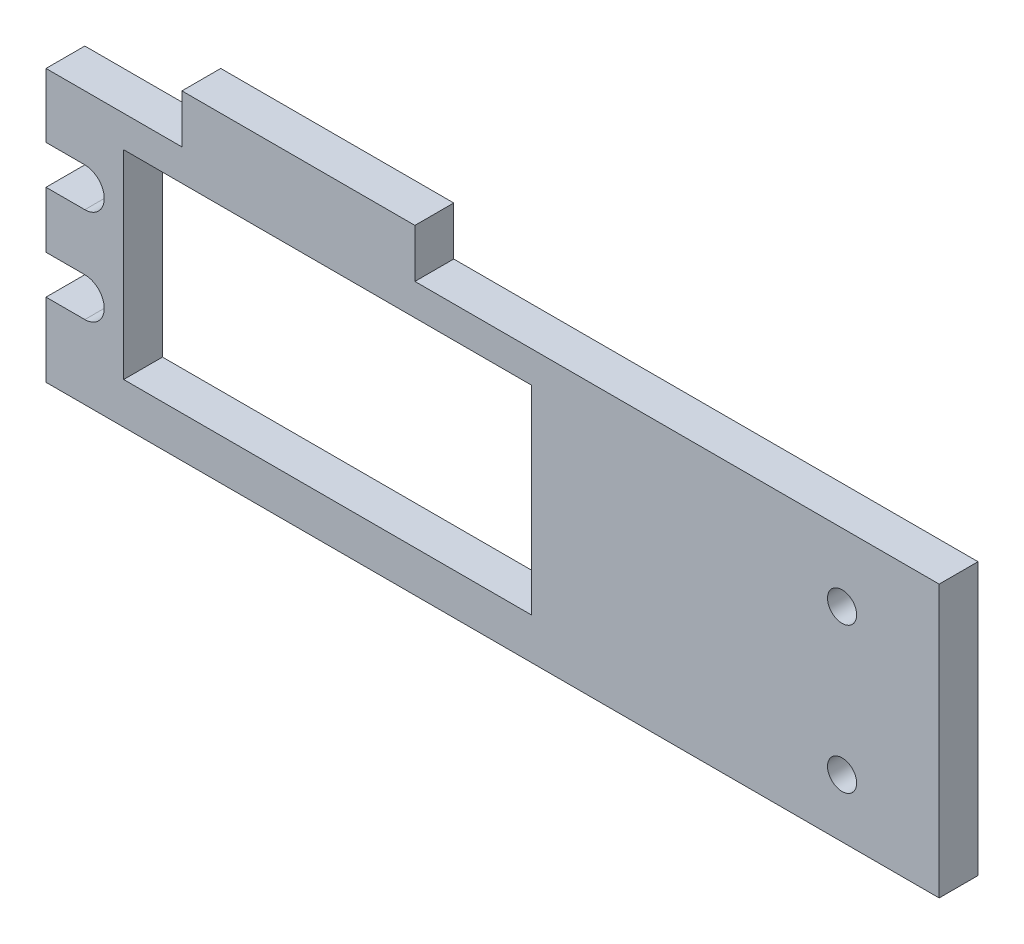
SolidWorks part; units mm, degrees
ref_plane "Front Plane" through (0, 0, 0) normal (0, 0, 1) x (1, 0, 0)
ref_plane "Top Plane" through (0, 0, 0) normal (0, 1, 0) x (1, 0, 0)
ref_plane "Right Plane" through (0, 0, 0) normal (1, 0, 0) x (0, 0, -1)
sketch "Sketch1" plane through (0, 0, 0) normal (0, 0, 1) x (1, 0, 0)
  line L0 (0, 0) -> (0, 28)
  line L1 (0, 28) -> (-54, 28)
  line L2 (-92, 28) -> (-92, 21.4)
  line L3 (-92, 21.4) -> (-88, 21.4)
  line L4 (-92, 17.4) -> (-88, 17.4)
  line L5 (-92, 17.4) -> (-92, 11.6)
  line L6 (-92, 11.6) -> (-88, 11.6)
  line L7 (-88, 7.6) -> (-92, 7.6)
  line L8 (-92, 7.6) -> (-92, 0)
  line L9 (-92, 0) -> (0, 0)
  line L10 (-78, 28) -> (-78, 33)
  line L11 (-78, 33) -> (-54, 33)
  line L12 (-54, 33) -> (-54, 28)
  line L13 (-78, 28) -> (-92, 28)
  line L15 (-84, 24.75) -> (-42, 24.75)
  line L16 (-84, 24.75) -> (-84, 4.25)
  line L17 (-84, 4.25) -> (-42, 4.25)
  line L18 (-42, 24.75) -> (-42, 4.25)
  arc A0 (-88, 21.4) -> (-88, 17.4) centre (-88, 19.4) cw
  arc A1 (-88, 11.6) -> (-88, 7.6) centre (-88, 9.6) cw
  circle A2 centre (-10, 21) radius 1.5
  circle A3 centre (-10, 6) radius 1.5
  dimension "D8" = 2
  dimension "D9" = 2
  dimension "D17" = 3
  dimension "D18" = 3
  dimension "D1" = 92
  dimension "D2" = 28
  dimension "D3" = 20.5
  dimension "D4" = 92
  dimension "D5" = 92
  dimension "D6" = 6.6
  dimension "D7" = 4
  dimension "D10" = 7.6
  dimension "D11" = 5
  dimension "D12" = 24
  dimension "D13" = 54
  dimension "D14" = 42
  dimension "D15" = 4.25
  dimension "D16" = 8
  dimension "D19" = 10
  dimension "D20" = 6
  dimension "D21" = 15
extrude "Boss-Extrude1" add sketch "Sketch1" along normal blind 4 contours L18 L15 L16 L17 | A2 | A3 | L1 L12 L11 L10 L13 L2 L3 A0 L4 L5 L6 A1 L7 L8 L9 L0
